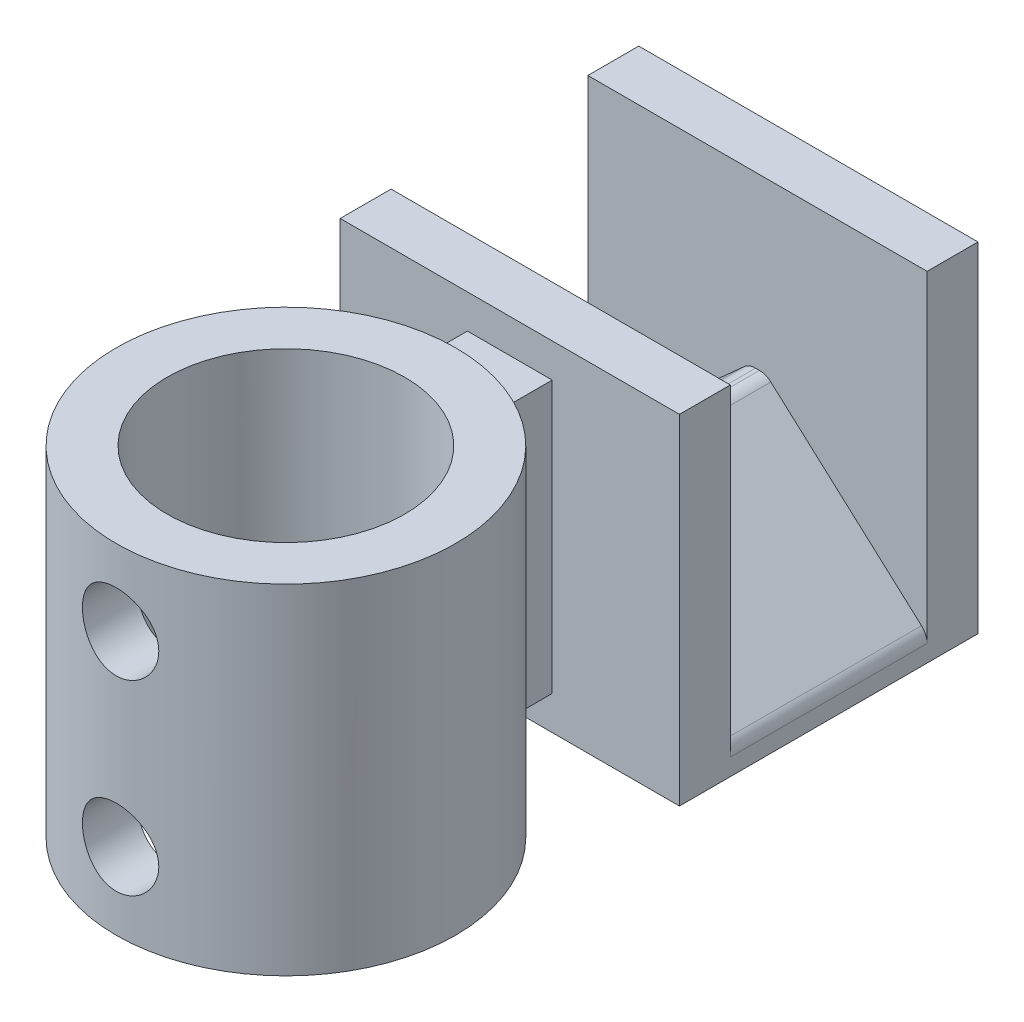
SolidWorks part; units mm, degrees
material "ABS"
ref_plane "Front Plane" through (0, 0, 0) normal (0, 0, 1) x (1, 0, 0)
ref_plane "Top Plane" through (0, 0, 0) normal (0, 1, 0) x (1, 0, 0)
ref_plane "Right Plane" through (0, 0, 0) normal (1, 0, 0) x (0, 0, -1)
sketch "Sketch2" plane through (0, 0, 0) normal (0, 0, 1) x (1, 0, 0)
  line L1 (-10, -5) -> (10, -5)
  line L2 (-10, -5) -> (-10, 5)
  line L3 (-10, 5) -> (10, 5)
  line L4 (10, -5) -> (10, 5)
  line L5 (-10, -5) -> (10, 5) construction
  line L6 (-10, 5) -> (10, -5) construction
  point P0 (0, 0)
  dimension "D1" = 10
  dimension "D2" = 20
extrude "Boss-Extrude1" add sketch "Sketch2" along normal mid plane 11.6
chamfer "Chamfer1" distance 9.5 angle 42 2 edges at (10, 5, 0) (-10, 5, 0)
fillet "Fillet3" radius 1 4 edges at (-10, -3.5538, 0) (10, -3.5538, 0) (0.5, 5, 0) (-0.5, 5, 0)
sketch "Sketch3" plane through (0, 0, 5.8) normal (0, 0, 1) x (1, 0, 0)
  line L0 (-10, -5) -> (10, -5) construction
  line L1 (-10, 15) -> (10, 15)
  line L2 (-10, 15) -> (-10, -5)
  line L3 (-10, -5) -> (10, -5)
  line L4 (10, 15) -> (10, -5)
  line L5 (-10, 15) -> (10, -5) construction
  line L6 (-10, -5) -> (10, 15) construction
  point P0 (0, 5)
  dimension "D1" = 20
  dimension "D2" = 20
extrude "Boss-Extrude2" add sketch "Sketch3" along normal blind 3
mirror "Mirror1" about plane through (0, 0, 0) normal (0, 0, 1) of "Boss-Extrude2"
sketch "Sketch6" plane through (0, 0, 0) normal (0, 1, 0) x (1, 0, 0)
  circle A0 centre (0, -22) radius 10
  circle A1 centre (0, -22) radius 7
  dimension "D1" = 14
  dimension "D2" = 3
  dimension "D3" = 22
extrude "Boss-Extrude3" add sketch "Sketch6" along normal up to surface and the other way up to surface separate body up to face at (0, 15, 7.3) other way up to face at (0, -5, 0)
sketch "Sketch5" plane through (0, 0, 8.8) normal (0, 0, 1) x (1, 0, 0)
  line L0 (-10, -5) -> (10, -5) construction
  line L1 (-2.5, 13) -> (2.5, 13)
  line L2 (-2.5, 13) -> (-2.5, -3)
  line L3 (-2.5, -3) -> (2.5, -3)
  line L4 (2.5, 13) -> (2.5, -3)
  line L5 (-2.5, 13) -> (2.5, -3) construction
  line L6 (-2.5, -3) -> (2.5, 13) construction
  line L7 (10, 15) -> (-10, 15) construction
  point P0 (0, 5)
  dimension "D1" = 2
  dimension "D2" = 2
  dimension "D3" = 5
extrude "Boss-Extrude4" add sketch "Sketch5" along normal up to surface (6.6617 mm away)
ref_plane "Plane1" through (0, 0, 20) normal (0, 0, 1) x (1, 0, 0)
sketch "Sketch7" plane through (0, 0, 20) normal (0, 0, 1) x (1, 0, 0)
  line L2 (-10, -5) -> (10, -5) construction
  line L3 (7, 15) -> (-7, 15) construction
  circle A0 centre (0, 10.5) radius 2.25
  circle A1 centre (0, -0.5) radius 2.25
  dimension "D1" = 4.5
  dimension "D2" = 4.5
  dimension "D3" = 4.5
  dimension "D4" = 4.5
extrude "Cut-Extrude1" cut sketch "Sketch7" along normal up to surface (11.7436 mm away)
equation "\"BEAM_WIDTH\" = 11.6mm"
equation "\"D1@Boss-Extrude1\"=\"BEAM_WIDTH\""
